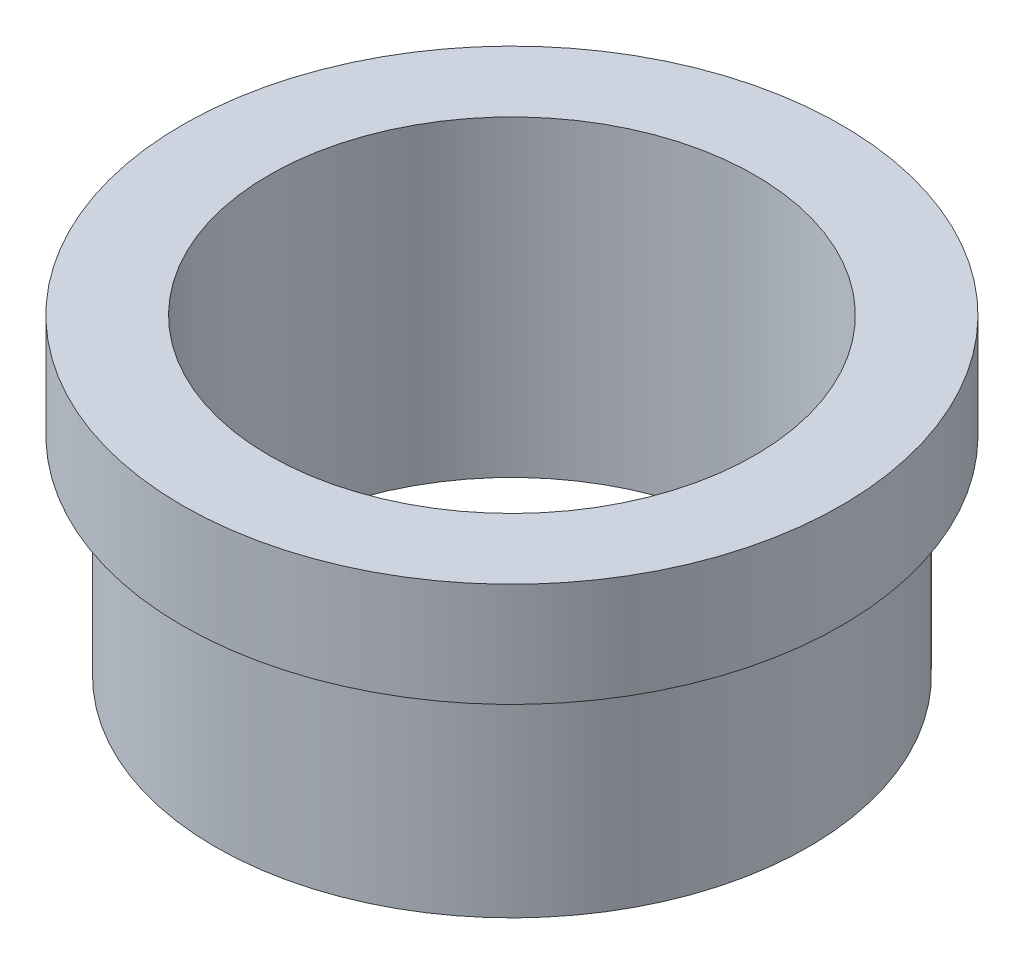
SolidWorks part; units mm, degrees
ref_plane "Alzado" through (0, 0, 0) normal (0, 0, 1) x (1, 0, 0)
ref_plane "Planta" through (0, 0, 0) normal (0, 1, 0) x (1, 0, 0)
ref_plane "Vista lateral" through (0, 0, 0) normal (1, 0, 0) x (0, 0, -1)
sketch "Sketch1" plane through (0, 0, 0) normal (0, 1, 0) x (1, 0, 0)
  circle A0 centre (0, 0) radius 7
  circle A1 centre (0, 0) radius 8.55
  dimension "D1" = 17.1
  dimension "D2" = 14
extrude "Boss-Extrude1" add sketch "Sketch1" along normal blind 6
sketch "Sketch2" plane through (0, 6, 0) normal (0, 1, 0) x (1, 0, 0)
  circle A0 centre (0, 0) radius 7
  circle A1 centre (0, 0) radius 9.5
  circle A2 centre (0, 0) radius 7 construction
  dimension "D1" = 19
extrude "Boss-Extrude2" add sketch "Sketch2" along normal blind 3
